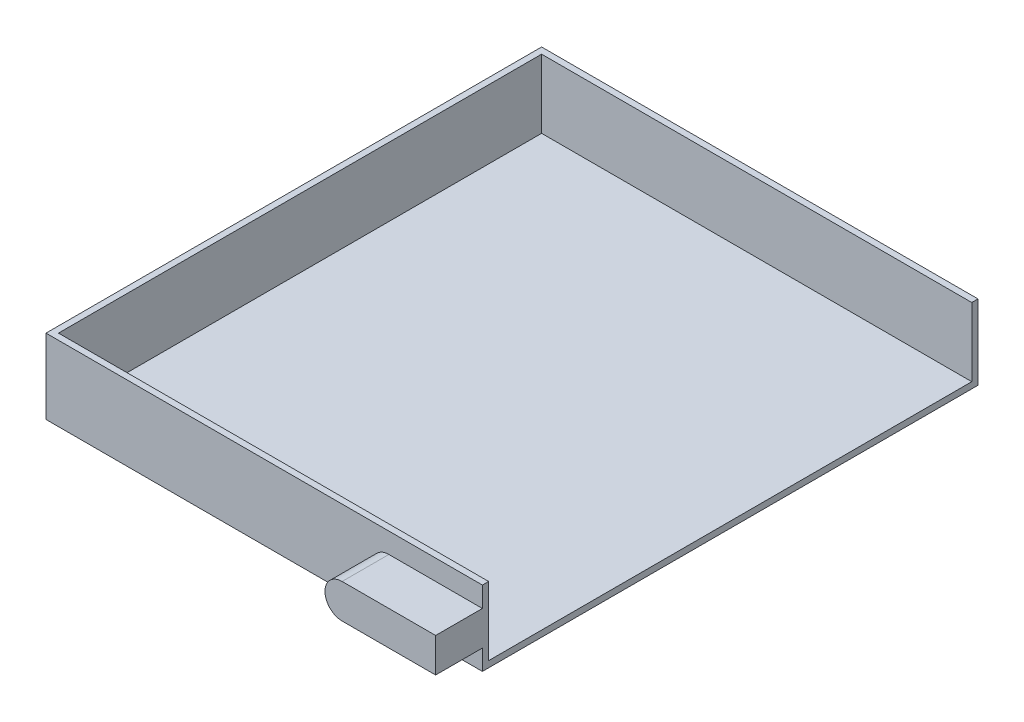
SolidWorks part; units mm, degrees
ref_plane "前视基准面" through (0, 0, 0) normal (0, 0, 1) x (1, 0, 0)
ref_plane "上视基准面" through (0, 0, 0) normal (0, 1, 0) x (1, 0, 0)
ref_plane "右视基准面" through (0, 0, 0) normal (1, 0, 0) x (0, 0, -1)
sketch "草图1" plane through (0, 0, 0) normal (0, 1, 0) x (1, 0, 0)
  line L1 (0, 0) -> (138, 0)
  line L2 (0, 0) -> (0, -155)
  line L3 (0, -155) -> (138, -155)
  line L4 (138, 0) -> (138, -155)
  dimension "D1" = 138
  dimension "D2" = 155
extrude "凸台-拉伸1" add sketch "草图1" along normal blind 22
shell "抽壳1" thickness 2
sketch "草图2" plane through (0, 0, 157) normal (0, 0, 1) x (1, 0, 0)
  line L0 (138, 22) -> (138, -2) construction
  line L1 (108, 10) -> (138, 10) construction
  line L2 (108, 15.5) -> (138, 15.5)
  line L3 (108, 4.5) -> (138, 4.5)
  line L4 (138, 15.5) -> (138, 4.5)
  arc A0 (108, 15.5) -> (108, 4.5) centre (108, 10) ccw
  point P0 (138, 10)
  point P1 (108, 10)
  point P4 (168, 10)
  point P7 (138, 10)
  dimension "D1" = 30
  dimension "D2" = 30
extrude "凸台-拉伸2" add sketch "草图2" along normal blind 15
